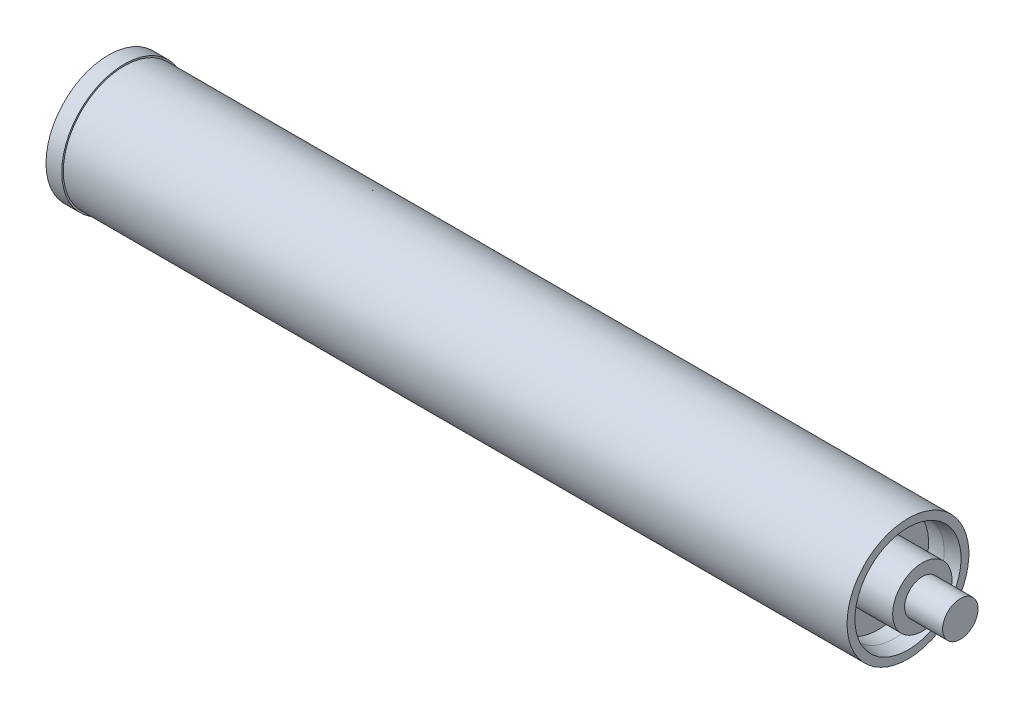
SolidWorks part; units mm, degrees
ref_plane "Plan de face" through (0, 0, 0) normal (0, 0, 1) x (1, 0, 0)
ref_plane "Plan de dessus" through (0, 0, 0) normal (0, 1, 0) x (1, 0, 0)
ref_plane "Plan de droite" through (0, 0, 0) normal (1, 0, 0) x (0, 0, -1)
sketch "Esquisse2" plane through (0, 0, 0) normal (0, 0, 1) x (1, 0, 0)
  line L0 (0, 0) -> (97.8436, 0) construction
  line L1 (0, -26) -> (0, 26) construction
  line L2 (0, 26) -> (12.7, 26)
  line L3 (12.7, 26) -> (12.7, 50.419) construction
  line L4 (12.7, 50.419) -> (25.4, 50.419)
  line L5 (25.4, 50.419) -> (25.4, 49.149)
  line L6 (25.4, 49.149) -> (657.7598, 49.149)
  line L7 (657.7598, 49.149) -> (657.7598, 42.8202)
  line L8 (657.7598, 42.8202) -> (646.4369, 40.5731)
  line L9 (646.4369, 40.5731) -> (633.8644, 40.5731)
  line L10 (633.8644, 40.5731) -> (633.8644, 23.9395)
  line L11 (633.8644, 23.9395) -> (669.3325, 23.9395)
  line L12 (669.3325, 23.9395) -> (669.3325, 14.2875)
  line L13 (669.3325, 14.2875) -> (700, 14.2875)
  line L14 (700, 14.2875) -> (700, -14.2875) construction
  line L15 (700, 0) -> (0, 0) construction
  line L16 (669.3325, -14.2875) -> (700, -14.2875) construction
  line L17 (669.3325, -23.9395) -> (669.3325, -14.2875) construction
  line L18 (633.8644, -23.9395) -> (669.3325, -23.9395) construction
  line L19 (633.8644, -40.5731) -> (633.8644, -23.9395) construction
  line L20 (646.4369, -40.5731) -> (633.8644, -40.5731) construction
  line L21 (657.7598, -42.8202) -> (646.4369, -40.5731) construction
  line L22 (657.7598, -49.149) -> (657.7598, -42.8202) construction
  line L23 (25.4, -49.149) -> (657.7598, -49.149) construction
  line L24 (25.4, -50.419) -> (25.4, -49.149) construction
  line L25 (12.7, -50.419) -> (25.4, -50.419) construction
  line L26 (12.7, -26) -> (12.7, -50.419) construction
  line L27 (0, -26) -> (12.7, -26) construction
  line L28 (12.7, 50.419) -> (12.7, 38.2095)
  line L29 (12.7, 38.2095) -> (25.4, 35.6891)
  line L30 (25.4, 35.6891) -> (36.5674, 35.6891)
  line L31 (36.5674, 35.6891) -> (36.5674, 26)
  line L32 (36.5674, 26) -> (12.7, 26)
  line L33 (25.4, 35.6891) -> (25.4, 49.149) construction
  line L34 (36.5674, -26) -> (12.7, -26) construction
  line L35 (36.5674, -35.6891) -> (36.5674, -26) construction
  line L36 (25.4, -35.6891) -> (36.5674, -35.6891) construction
  line L37 (12.7, -38.2095) -> (25.4, -35.6891) construction
  line L38 (12.7, -50.419) -> (12.7, -38.2095) construction
  line L39 (0, 26) -> (0, 0)
  line L40 (0, 0) -> (700, 0)
  line L41 (700, 0) -> (700, 14.2875)
  dimension "D2" = 30.6675
  dimension "D3" = 42.2402
  dimension "D4" = 28.575
  dimension "D5" = 47.879
  dimension "D6" = 98.298
  dimension "D7" = 12.7
  dimension "D8" = 100.838
  dimension "D9" = 12.7
  dimension "D10" = 52
  dimension "D11" = 66.1356
  dimension "D12" = 12.5725
  dimension "D13" = 16.6336
  dimension "D14" = 11.5437
  dimension "D15" = 36.5674
  dimension "D16" = 700
revolve "Révolution7" add sketch "Esquisse2" angle 360 about L0
sketch "Esquisse3" plane through (0, 0, 0) normal (0, 0, 1) x (1, 0, 0)
  line L0 (0, 0) -> (700, 0) construction
  line L1 (700, -14.2875) -> (700, 14.2875) construction
  line L2 (0, 20) -> (0, 0)
  line L3 (0, 26) -> (0, -26) construction
  line L4 (0, 0) -> (633.8644, 0)
  line L5 (633.8644, 0) -> (633.8644, 12.9578)
  line L6 (633.8644, -40.5731) -> (633.8644, 40.5731) construction
  line L7 (633.8644, 12.9578) -> (616.5139, 12.9578)
  line L8 (616.5139, 12.9578) -> (616.5139, 44.271)
  line L9 (616.5139, 44.271) -> (65.8719, 44.271)
  line L10 (65.8719, 44.271) -> (34.083, 14.3276)
  line L11 (34.083, 14.3276) -> (19.083, 14.3276)
  line L12 (19.083, 14.3276) -> (0, 20)
  line L13 (36.5674, 26) -> (0, 26) construction
  point P19 (633.8644, 0)
  point P20 (657.772, 0)
  dimension "D1" = 15
  dimension "D2" = 6
  dimension "D3" = 17.3505
  dimension "D4" = 19.083
  dimension "D5" = 19.9082
  dimension "D6" = 43.6708
  dimension "D7" = 29.9434
  dimension "D8" = 12.9578
revolve "Enlèvement de matière-Révolution1" cut sketch "Esquisse3" angle 360 about L0
